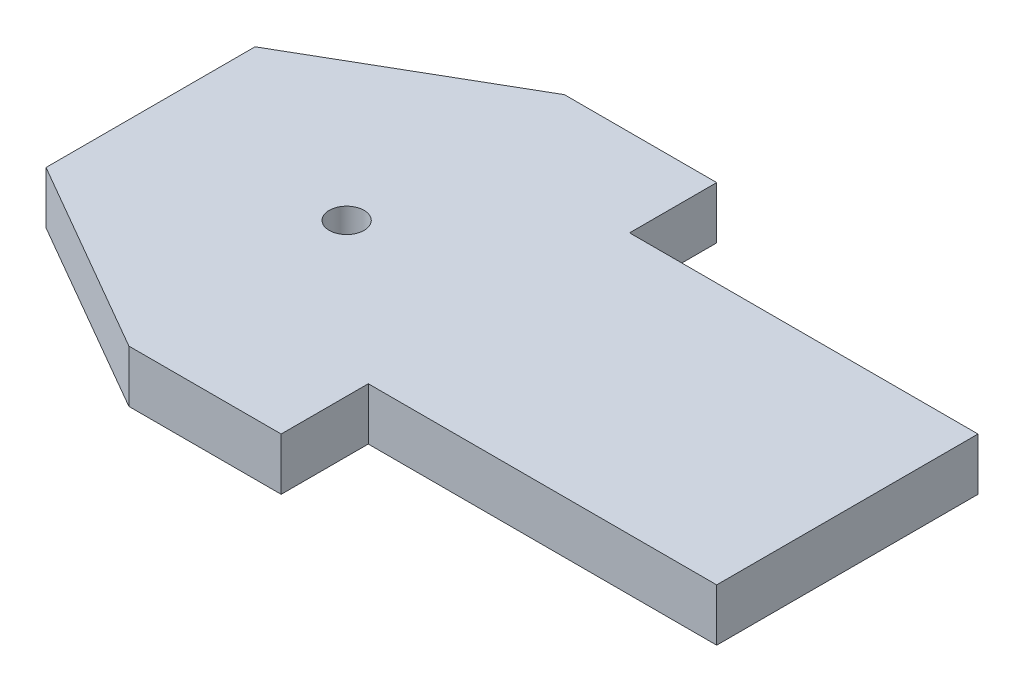
SolidWorks part; units mm, degrees
ref_plane "Front Plane" through (0, 0, 0) normal (0, 0, 1) x (1, 0, 0)
ref_plane "Top Plane" through (0, 0, 0) normal (0, 1, 0) x (1, 0, 0)
ref_plane "Right Plane" through (0, 0, 0) normal (1, 0, 0) x (0, 0, -1)
sketch "Sketch1" plane through (0, 0, 0) normal (0, 1, 0) x (1, 0, 0)
  line L0 (-10, 7.5) -> (-10, 12.5)
  line L1 (-10, 7.5) -> (10, 7.5)
  line L3 (-10, -7.5) -> (10, -7.5)
  line L4 (10, 7.5) -> (10, -7.5)
  line L5 (-10, 7.5) -> (10, -7.5) construction
  line L6 (-10, -7.5) -> (10, 7.5) construction
  line L7 (-10, 12.5) -> (-18.7417, 12.5)
  line L8 (-30, 6) -> (-18.7417, 12.5)
  line L9 (-30, 6) -> (-30, -6)
  line L10 (-30, -6) -> (-18.7417, -12.5)
  line L11 (-18.7417, -12.5) -> (-10, -12.5)
  line L12 (-10, -12.5) -> (-10, -7.5)
  point P0 (0, 0)
  dimension "D1" = 15
  dimension "D3" = 5
  dimension "D4" = 5
  dimension "D6" = 30
  dimension "D7" = 30
  dimension "D8" = 12
  dimension "D9" = 13
extrude "Boss-Extrude1" add sketch "Sketch1" along normal blind 3
sketch "Sketch2" plane through (0, 3, 0) normal (0, 1, 0) x (1, 0, 0)
  circle A0 centre (-18.7417, 0) radius 1
  dimension "D1" = 2
extrude "Cut-Extrude1" cut sketch "Sketch2" against normal blind 33
